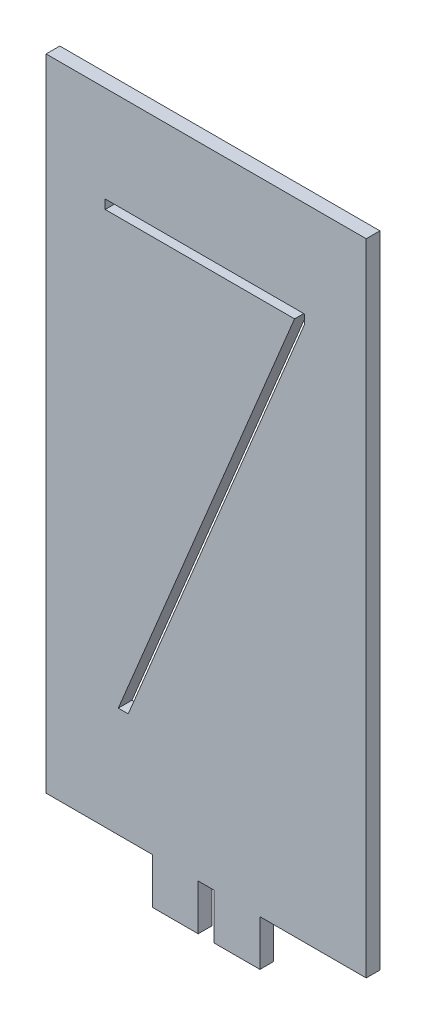
SolidWorks part; units mm, degrees
material "Glas"
ref_plane "Ebene vorne" through (0, 0, 0) normal (0, 0, 1) x (1, 0, 0)
ref_plane "Ebene oben" through (0, 0, 0) normal (0, 1, 0) x (1, 0, 0)
ref_plane "Ebene rechts" through (0, 0, 0) normal (1, 0, 0) x (0, 0, -1)
sketch "Skizze1" plane through (0, 0, 0) normal (0, 0, 1) x (1, 0, 0)
  line L1 (0, 0) -> (35, 0)
  line L2 (0, 0) -> (0, 75)
  line L3 (0, 75) -> (35, 75)
  line L4 (35, 0) -> (35, 75)
  dimension "D1" = 35
  dimension "D2" = 75
extrude "Aufsatz-Linear austragen1" add sketch "Skizze1" along normal blind 1.5
sketch "Skizze2" plane through (0, 0, 1.5) normal (0, 0, 1) x (1, 0, 0)
  line L0 (0, 0) -> (35, 0) construction
  line L1 (0, 0) -> (11.63, 0)
  line L2 (0, 0) -> (0, 5)
  line L3 (0, 5) -> (11.63, 5)
  line L4 (11.63, 0) -> (11.63, 5)
  line L5 (23.38, 5) -> (35, 5)
  line L6 (23.38, 5) -> (23.38, 0)
  line L7 (23.38, 0) -> (35, 0)
  line L8 (35, 5) -> (35, 0)
  line L9 (16.63, 0) -> (18.38, 0)
  line L10 (16.63, 0) -> (16.63, 5)
  line L11 (16.63, 5) -> (18.38, 5)
  line L12 (18.38, 0) -> (18.38, 5)
  dimension "D1" = 5
  dimension "D2" = 5
  dimension "D3" = 5
  dimension "D4" = 11.63
  dimension "D5" = 1.75
  dimension "D6" = 5
extrude "Schnitt-Linear austragen1" cut sketch "Skizze2" against normal blind 1.5
sketch "Skizze12" plane through (0, 0, 1.5) normal (0, 0, 1) x (1, 0, 0)
  line L0 (6.4592, 64.5) -> (28.25, 64.5)
  line L1 (28.25, 64.5) -> (28.25, 63.5)
  line L2 (28.25, 63.5) -> (8.9767, 17)
  line L3 (8.9767, 17) -> (7.8942, 17)
  line L4 (7.8942, 17) -> (27.1675, 63.5)
  line L5 (27.1675, 63.5) -> (6.4592, 63.5)
  line L6 (6.4592, 63.5) -> (6.4592, 64.5)
  line L7 (35, 75) -> (0, 75) construction
  line L10 (35, 5) -> (35, 75) construction
  dimension "D1" = 1
  dimension "D2" = 1
  dimension "D3" = 10.5
  dimension "D4" = 1
  dimension "D5" = 1
  dimension "D6" = 46.5
  dimension "D7" = 6.75
extrude "Schnitt-Linear austragen7" cut sketch "Skizze12" against normal blind 20
